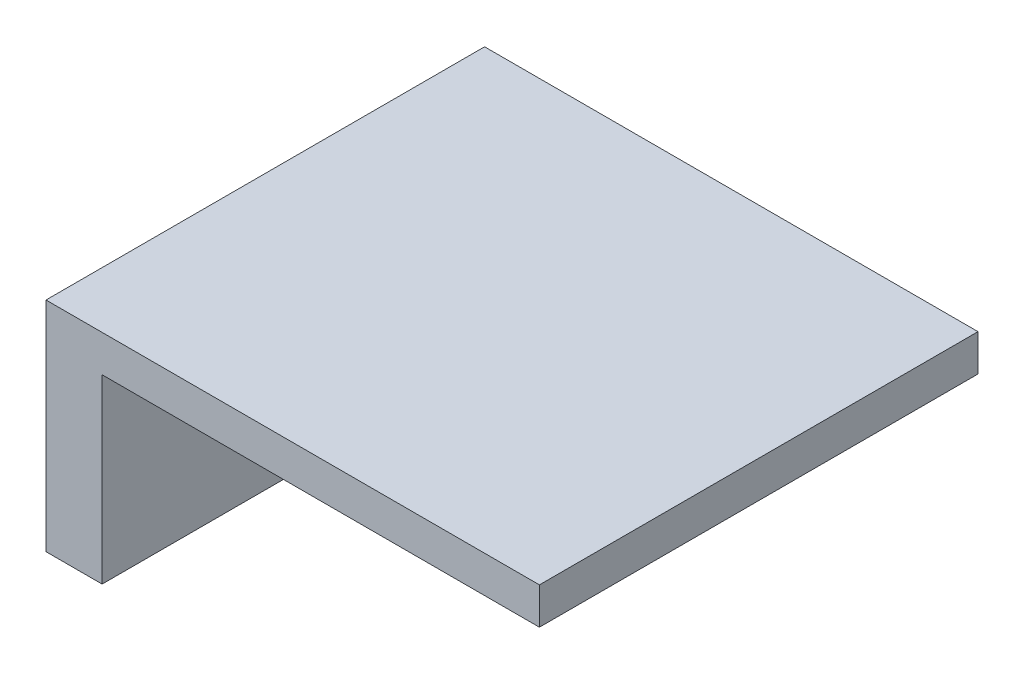
SolidWorks part; units mm, degrees
ref_plane "Front Plane" through (0, 0, 0) normal (0, 0, 1) x (1, 0, 0)
ref_plane "Top Plane" through (0, 0, 0) normal (0, 1, 0) x (1, 0, 0)
ref_plane "Right Plane" through (0, 0, 0) normal (1, 0, 0) x (0, 0, -1)
sketch "Sketch1" plane through (0, 0, 0) normal (0, 1, 0) x (1, 0, 0)
  line L1 (-29.6389, -14.9911) -> (-6.7789, -14.9911)
  line L2 (-29.6389, -14.9911) -> (-29.6389, 5.3289)
  line L3 (-29.6389, 5.3289) -> (-6.7789, 5.3289)
  line L4 (-6.7789, -14.9911) -> (-6.7789, 5.3289)
  dimension "D1" = 22.86
  dimension "D2" = 20.32
extrude "Extrude1" add sketch "Sketch1" along normal blind 1.7
sketch "Sketch2" plane through (0, 0, 0) normal (0, -1, 0) x (1, 0, 0)
  line L0 (-6.7789, -5.3289) -> (-29.6389, -5.3289) construction
  line L1 (-29.6389, 14.9911) -> (-27.0389, 14.9911)
  line L2 (-29.6389, 14.9911) -> (-29.6389, -5.3289)
  line L3 (-29.6389, -5.3289) -> (-27.0389, -5.3289)
  line L4 (-27.0389, 14.9911) -> (-27.0389, -5.3289)
  dimension "D1" = 2.6
extrude "Extrude2" add sketch "Sketch2" along normal blind 8.4
